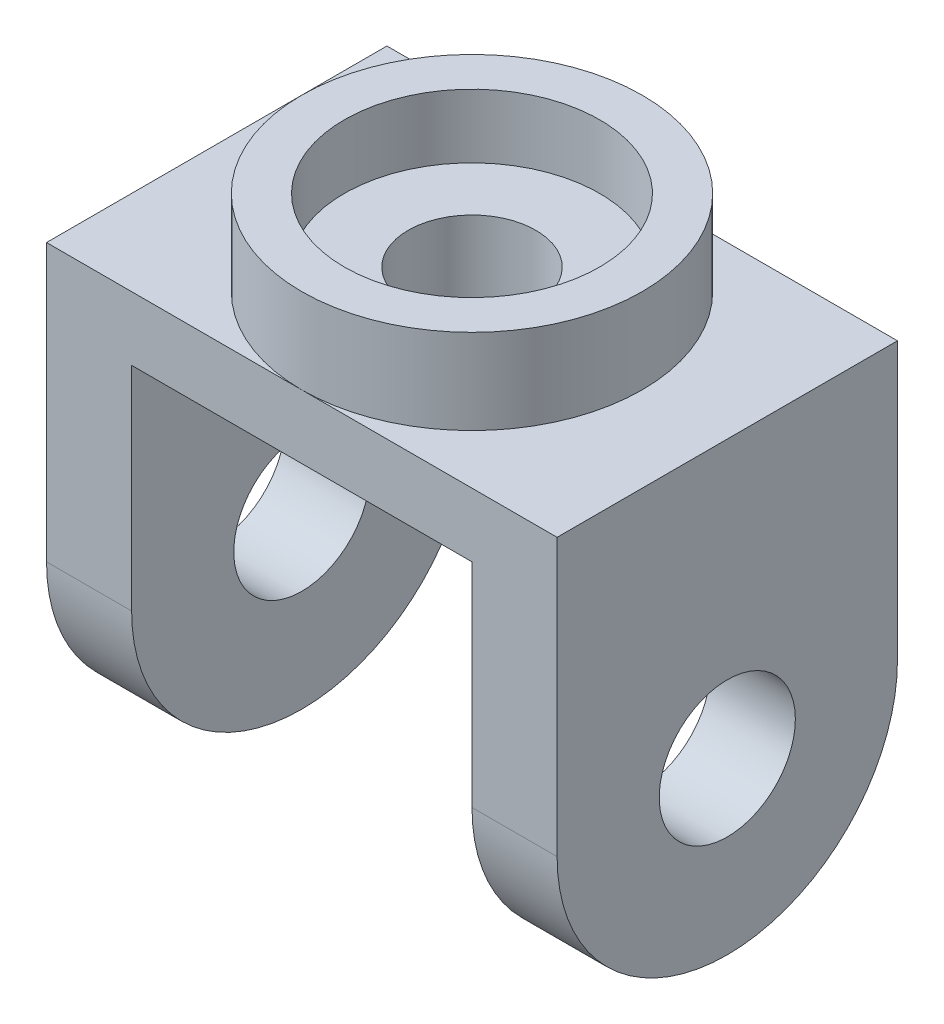
SolidWorks part; units mm, degrees
ref_plane "Ön Düzlem" through (0, 0, 0) normal (0, 0, 1) x (1, 0, 0)
ref_plane "Üst Düzlem" through (0, 0, 0) normal (0, 1, 0) x (1, 0, 0)
ref_plane "Sağ Düzlem" through (0, 0, 0) normal (1, 0, 0) x (0, 0, -1)
sketch "Sketch1" plane through (0, 0, 0) normal (0, 1, 0) x (1, 0, 0)
  line L1 (-60, -40) -> (60, -40)
  line L2 (-60, -40) -> (-60, 40)
  line L3 (-60, 40) -> (60, 40)
  line L4 (60, -40) -> (60, 40)
  line L5 (-60, -40) -> (60, 40) construction
  line L6 (-60, 40) -> (60, -40) construction
  point P0 (0, 0)
  dimension "D1" = 120
  dimension "D2" = 80
extrude "Boss-Extrude1" add sketch "Sketch1" along normal blind 15
sketch "Sketch2" plane through (0, 15, 0) normal (0, 1, 0) x (1, 0, 0)
  circle A0 centre (0, 0) radius 40
  dimension "D1" = 80
extrude "Boss-Extrude2" add sketch "Sketch2" along normal blind 20
sketch "Sketch3" plane through (0, 35, 0) normal (0, 1, 0) x (1, 0, 0)
  circle A0 centre (0, 0) radius 30
  dimension "D1" = 60
extrude "Cut-Extrude1" cut sketch "Sketch3" against normal blind 15
sketch "Sketch4" plane through (0, 20, 0) normal (0, 1, 0) x (1, 0, 0)
  circle A0 centre (0, 0) radius 15
  dimension "D1" = 30
extrude "Cut-Extrude2" cut sketch "Sketch4" against normal through all
sketch "Sketch5" plane through (60, 0, 0) normal (1, 0, 0) x (0, 0, -1)
  line L2 (40, -50) -> (40, 0)
  line L3 (40, 0) -> (-40, 0)
  line L4 (-40, -50) -> (-40, 0)
  arc A0 (-40, -50) -> (40, -50) centre (0, -50) ccw
  circle A1 centre (0, -50) radius 16
  dimension "D2" = 40
  dimension "D3" = 32
  dimension "D1" = 50
extrude "Boss-Extrude3" add sketch "Sketch5" against normal blind 20
mirror "Mirror1" about plane through (0, 0, 0) normal (1, 0, 0) of "Boss-Extrude3"
